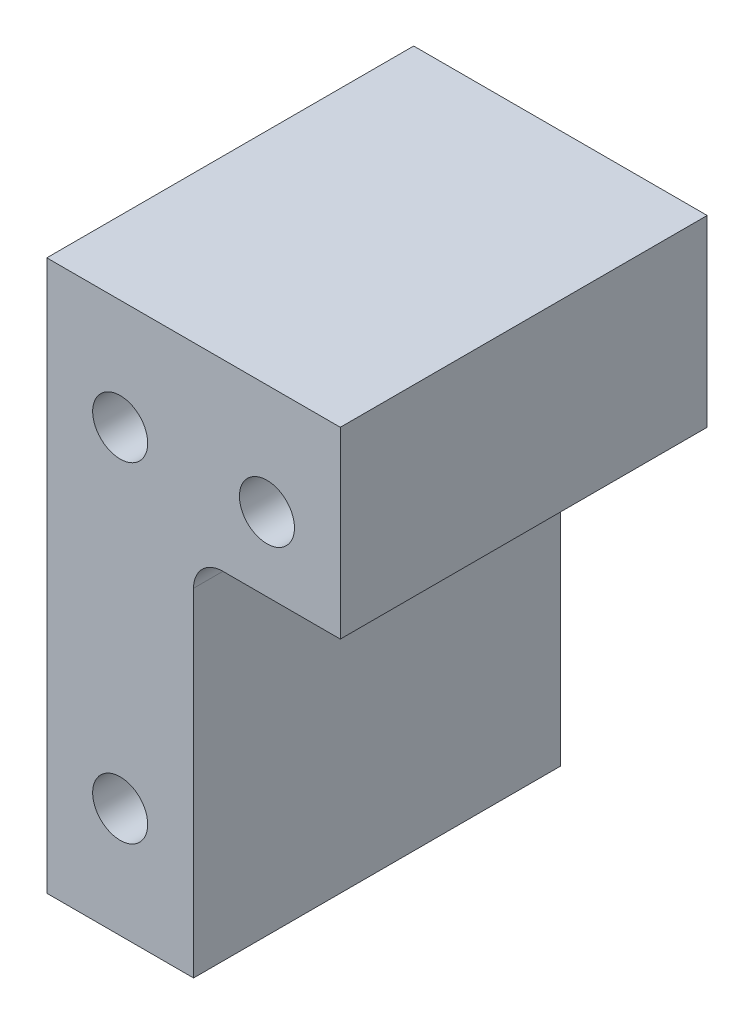
SolidWorks part; units mm, degrees
ref_plane "Front Plane" through (0, 0, 0) normal (0, 0, 1) x (1, 0, 0)
ref_plane "Top Plane" through (0, 0, 0) normal (0, 1, 0) x (1, 0, 0)
ref_plane "Right Plane" through (0, 0, 0) normal (1, 0, 0) x (0, 0, -1)
sketch "Sketch1" plane through (0, 0, 0) normal (0, 0, 1) x (1, 0, 0)
  line L0 (0, 0) -> (0, 38.1)
  line L1 (0, 38.1) -> (20.32, 38.1)
  line L2 (20.32, 38.1) -> (20.32, 25.4)
  line L3 (20.32, 25.4) -> (12.192, 25.4)
  line L4 (10.16, 23.368) -> (10.16, 0)
  line L5 (10.16, 0) -> (0, 0)
  line L6 (5.08, 0) -> (5.08, 7.62) construction
  circle A0 centre (5.08, 30.48) radius 1.905
  circle A1 centre (5.08, 7.62) radius 1.905
  circle A2 centre (15.24, 30.48) radius 1.905
  arc A3 (12.192, 25.4) -> (10.16, 23.368) centre (12.192, 23.368) ccw
  point P14 (12.319, 30.48)
  point P15 (0, 0)
  point P16 (0, 0)
  point P17 (0, 0)
  point P20 (10.16, 25.4)
  dimension "D1" = 3.81
  dimension "D2" = 5.08
  dimension "D8" = 2.032
  dimension "D3" = 7.62
  dimension "D4" = 7.62
  dimension "D5" = 22.86
  dimension "D6" = 12.7
  dimension "D7" = 5.08
  dimension "D9" = 20.32
extrude "Boss-Extrude1" add sketch "Sketch1" along normal blind 25.4
